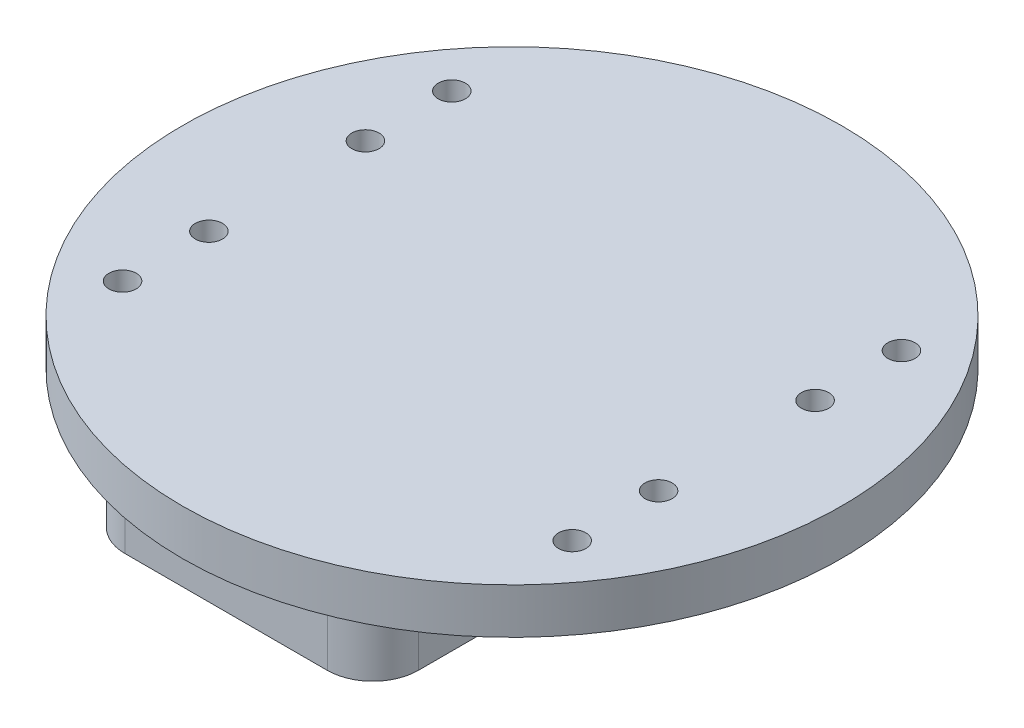
SolidWorks part; units mm, degrees
ref_plane "Front Plane" through (0, 0, 0) normal (0, 0, 1) x (1, 0, 0)
ref_plane "Top Plane" through (0, 0, 0) normal (0, 1, 0) x (1, 0, 0)
ref_plane "Right Plane" through (0, 0, 0) normal (1, 0, 0) x (0, 0, -1)
sketch "Sketch1" plane through (0, 0, 0) normal (0, 1, 0) x (1, 0, 0)
  circle A0 centre (0, 0) radius 72.5
  dimension "D1" = 145
extrude "Boss-Extrude1" add sketch "Sketch1" along normal blind 10
sketch "Sketch2" plane through (0, 0, 0) normal (0, -1, 0) x (1, 0, 0)
  line L1 (-22.2469, 62.8651) -> (22.2469, 62.8651)
  line L2 (-32.2469, 52.8651) -> (-32.2469, 15.5362)
  line L3 (-32.2469, 15.5362) -> (32.2469, 15.5362)
  line L4 (32.2469, 52.8651) -> (32.2469, 15.5362)
  line L5 (-32.2469, 62.8651) -> (32.2469, 15.5362) construction
  line L6 (-32.2469, 15.5362) -> (32.2469, 62.8651) construction
  arc A0 (32.2469, 52.8651) -> (22.2469, 62.8651) centre (22.2469, 52.8651) ccw
  arc A1 (-22.2469, 62.8651) -> (-32.2469, 52.8651) centre (-22.2469, 52.8651) ccw
  point P0 (0, 39.2007)
  point P11 (0, 15.5362)
  dimension "D1" = 10
extrude "Boss-Extrude2" add sketch "Sketch2" along normal blind 15
mirror "Mirror1" about plane through (0, 0, 0) normal (0, 0, 1) of "Boss-Extrude2"
sketch "Sketch3" plane through (0, 0, 0) normal (0, -1, 0) x (1, 0, 0)
  circle A0 centre (-49.4583, 36.216) radius 3
  circle A1 centre (-49.4583, 17.216) radius 3
  dimension "D1" = 6
  dimension "D2" = 2
extrude "Cut-Extrude1" cut sketch "Sketch3" against normal blind 10
mirror "Mirror2" about plane through (0, 0, 0) normal (0, 0, 1) of "Cut-Extrude1"
mirror "Mirror3" about plane through (0, 0, 0) normal (1, 0, 0) of "Mirror2", "Cut-Extrude1"
